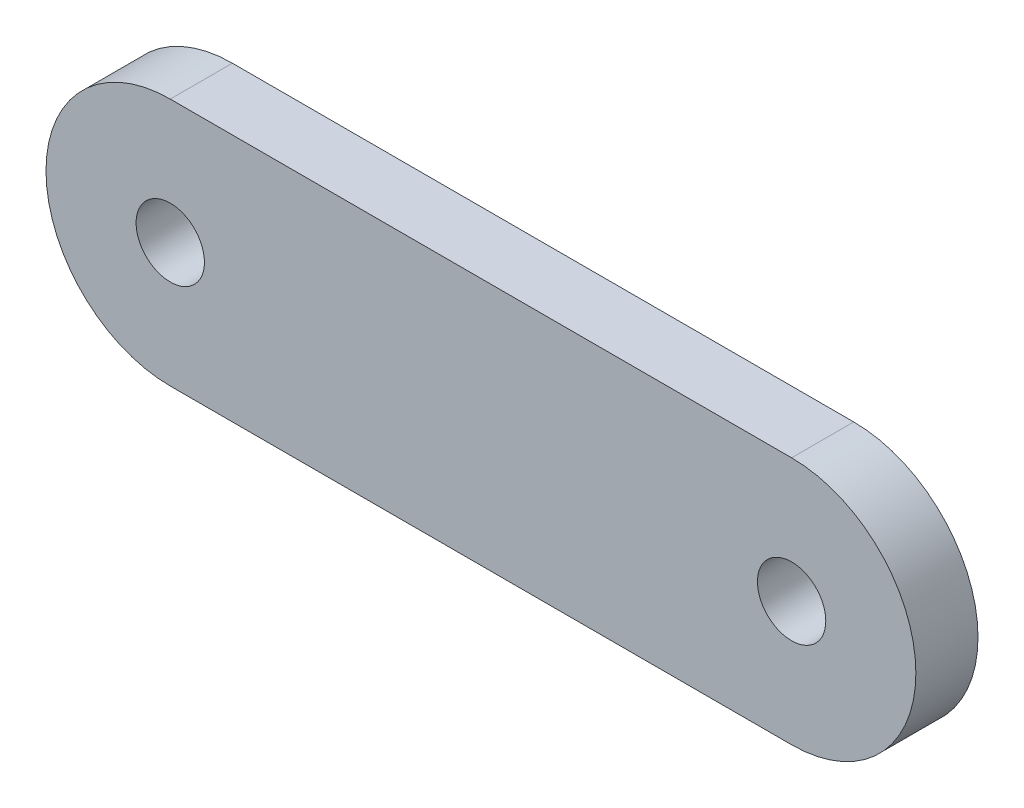
SolidWorks part; units mm, degrees
material "PA Type 6"
ref_plane "Front Plane" through (0, 0, 0) normal (0, 0, 1) x (1, 0, 0)
ref_plane "Top Plane" through (0, 0, 0) normal (0, 1, 0) x (1, 0, 0)
ref_plane "Right Plane" through (0, 0, 0) normal (1, 0, 0) x (0, 0, -1)
sketch "Sketch1" plane through (0, 0, 0) normal (0, 0, 1) x (1, 0, 0)
  line L0 (0, 0) -> (100, 0)
  line L1 (100, 40) -> (0, 40)
  arc A1 (100, 0) -> (100, 40) centre (100, 20) ccw
  arc A2 (0, 40) -> (0, 0) centre (0, 20) ccw
  circle A3 centre (0, 20) radius 5.5
  circle A4 centre (100, 20) radius 5.5
  dimension "D1" = 11
  dimension "D2" = 20
  dimension "D3" = 11
  dimension "D4" = 100
extrude "Boss-Extrude1" add sketch "Sketch1" along normal blind 10
